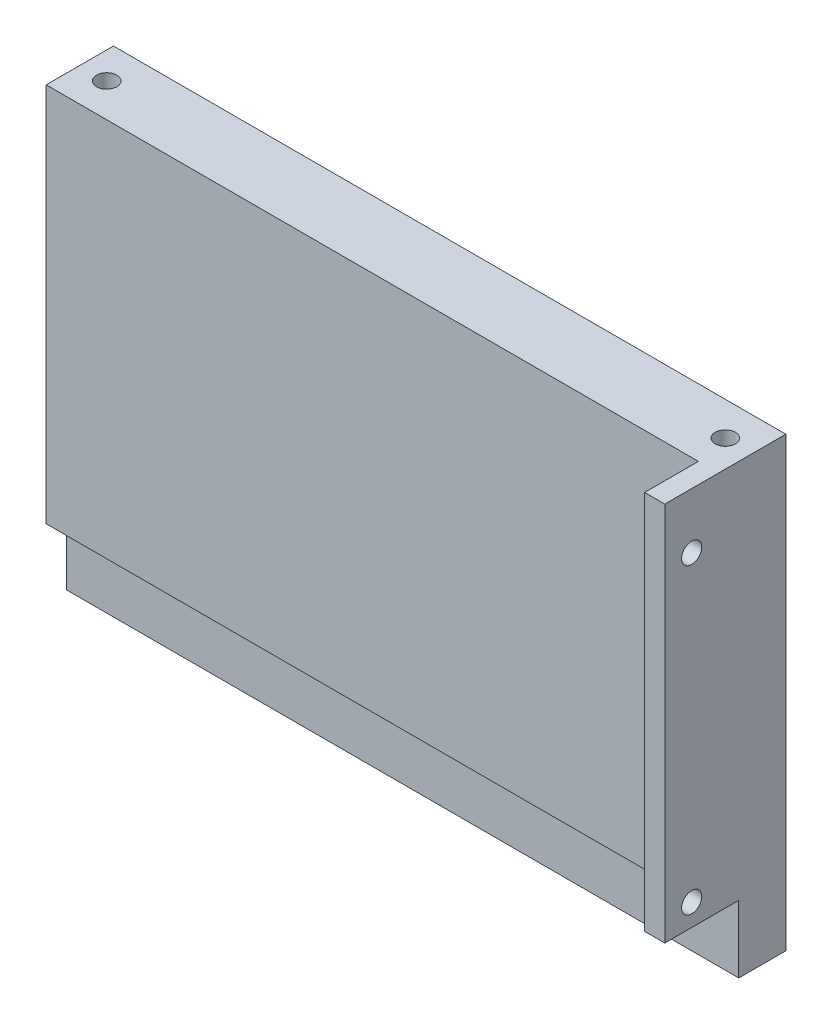
SolidWorks part; units mm, degrees
ref_plane "Front Plane" through (0, 0, 0) normal (0, 0, 1) x (1, 0, 0)
ref_plane "Top Plane" through (0, 0, 0) normal (0, 1, 0) x (1, 0, 0)
ref_plane "Right Plane" through (0, 0, 0) normal (1, 0, 0) x (0, 0, -1)
sketch "Sketch1" plane through (0, 0, 0) normal (0, 1, 0) x (1, 0, 0)
  line L1 (-50, -5) -> (50, -5)
  line L2 (-50, -5) -> (-50, 5)
  line L3 (-50, 5) -> (50, 5)
  line L4 (50, -5) -> (50, 5)
  line L5 (-50, -5) -> (50, 5) construction
  line L6 (-50, 5) -> (50, -5) construction
  point P0 (0, 0)
  dimension "D1" = 100
  dimension "D2" = 10
extrude "Boss-Extrude1" add sketch "Sketch1" along normal blind 66.54
sketch "Sketch2" plane through (0, 66.54, 0) normal (0, 1, 0) x (1, 0, 0)
  line L0 (-50, 5) -> (-50, -5) construction
  line L1 (-50, -5) -> (50, -5) construction
  circle A0 centre (-46, 0) radius 1.5
  dimension "D1" = 3
  dimension "D2" = 4
  dimension "D3" = 5
extrude "Cut-Extrude1" cut sketch "Sketch2" against normal up to next
pattern_linear "LPattern1" count 2 spacing 92 along (1, 0, 0) of "Cut-Extrude1"
sketch "Sketch3" plane through (0, 0, 5) normal (0, 0, 1) x (1, 0, 0)
  line L0 (50, 66.54) -> (50, 0) construction
  line L1 (-50, 0) -> (50, 0)
  line L2 (-50, 0) -> (-50, 10)
  line L3 (-50, 10) -> (50, 10)
  line L4 (50, 0) -> (50, 10)
  dimension "D1" = 10
extrude "Cut-Extrude2" cut sketch "Sketch3" against normal blind 3
sketch "Sketch4" plane through (0, 0, 5) normal (0, 0, 1) x (1, 0, 0)
  line L0 (50, 10) -> (-50, 10) construction
  line L1 (50, 66.54) -> (47, 66.54)
  line L2 (50, 66.54) -> (50, 10)
  line L3 (50, 10) -> (47, 10)
  line L4 (47, 66.54) -> (47, 10)
  dimension "D1" = 3
extrude "Boss-Extrude2" add sketch "Sketch4" along normal blind 8
sketch "Sketch5" plane through (50, 0, 0) normal (1, 0, 0) x (0, 0, -1)
  line L1 (-13, 66.54) -> (5, 66.54) construction
  line L2 (-13, 10) -> (-13, 66.54) construction
  circle A0 centre (-9, 58.27) radius 1.5
  circle A1 centre (-9, 13.27) radius 1.5
  point P4 (0, 0)
  point P6 (-9.7617, 63.2846)
  dimension "D1" = 3
  dimension "D2" = 3
  dimension "D3" = 45
  dimension "D4" = 8.27
  dimension "D5" = 4
extrude "Cut-Extrude3" cut sketch "Sketch5" against normal up to next
